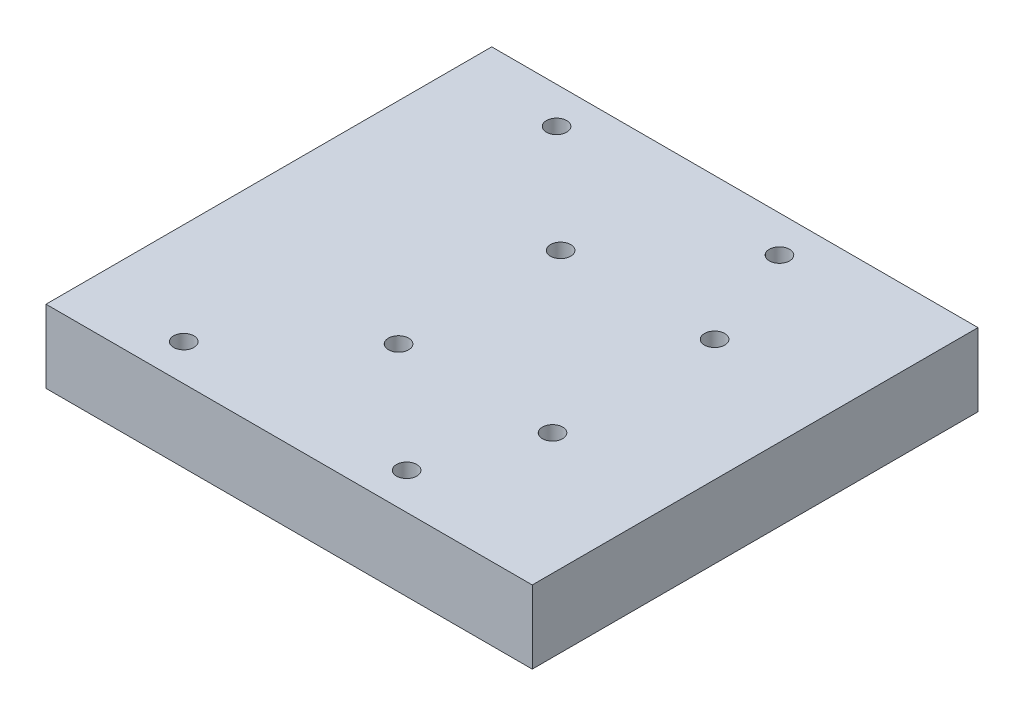
SolidWorks part; units mm, degrees
ref_plane "Front Plane" through (0, 0, 0) normal (0, 0, 1) x (1, 0, 0)
ref_plane "Top Plane" through (0, 0, 0) normal (0, 1, 0) x (1, 0, 0)
ref_plane "Right Plane" through (0, 0, 0) normal (1, 0, 0) x (0, 0, -1)
sketch "Sketch1" plane through (0, 0, 0) normal (0, 1, 0) x (1, 0, 0)
  line L1 (-60, 55) -> (60, 55)
  line L2 (-60, 55) -> (-60, -55)
  line L3 (-60, -55) -> (60, -55)
  line L4 (60, 55) -> (60, -55)
  line L5 (-60, 55) -> (60, -55) construction
  line L6 (-60, -55) -> (60, 55) construction
  point P0 (0, 0)
  dimension "D1" = 110
  dimension "D2" = 120
extrude "Boss-Extrude1" add sketch "Sketch1" along normal blind 18
hole_wizard "Ø5.0 (5) Diameter Hole1" positions "Sketch3" profile "Sketch2" hole size "Ø5.0" standard "ISO" end condition through all
sketch "Sketch3" plane through (0, 0, 0) normal (0, -1, 0) x (-1, 0, 0)
  line L0 (-60, 55) -> (60, 55) construction
  line L1 (60, -55) -> (-60, -55) construction
  line L2 (60, 55) -> (60, -55) construction
  point P0 (-20, 46)
  point P2 (35, 46)
  point P4 (35, -46)
  point P6 (-20, -46)
  dimension "D1" = 9
  dimension "D2" = 9
  dimension "D3" = 9
  dimension "D4" = 9
  dimension "D5" = 55
  dimension "D6" = 25
  dimension "D7" = 55
  dimension "D8" = 25
sketch "Sketch2" plane through (20, 0, -46) normal (1, 0, 0) x (0, 0, -1)
  line L0 (0, 0) -> (0, 18)
  line L1 (0, 18) -> (2.5, 18)
  line L2 (2.5, 18) -> (2.5, 0)
  line L5 (2.5, 0) -> (0, 0)
  line L11 (0, -6.35) -> (0, 107.95) construction
  dimension "Thru Hole Dia." = 5
  dimension "Thru Hole Depth" = 18
hole_wizard "Ø5.0 (5) Diameter Hole3" positions "Sketch7" profile "Sketch6" hole size "Ø5.0" standard "ISO" end condition through all
sketch "Sketch7" plane through (0, 0, 0) normal (0, -1, 0) x (-1, 0, 0)
  line L0 (60, -55) -> (-60, -55) construction
  line L1 (-60, 55) -> (60, 55) construction
  line L2 (-60, -55) -> (-60, 55) construction
  point P0 (8, 20)
  point P2 (-30, 20)
  point P4 (-30, -20)
  point P6 (8, -20)
  dimension "D1" = 35
  dimension "D2" = 35
  dimension "D3" = 35
  dimension "D4" = 35
  dimension "D5" = 30
  dimension "D6" = 30
  dimension "D7" = 38
  dimension "D8" = 38
sketch "Sketch6" plane through (-8, 0, -20) normal (1, 0, 0) x (0, 0, -1)
  line L0 (0, 0) -> (0, 18)
  line L1 (0, 18) -> (2.5, 18)
  line L2 (2.5, 18) -> (2.5, 0)
  line L5 (2.5, 0) -> (0, 0)
  line L11 (0, -6.35) -> (0, 107.95) construction
  dimension "Thru Hole Dia." = 5
  dimension "Thru Hole Depth" = 18
